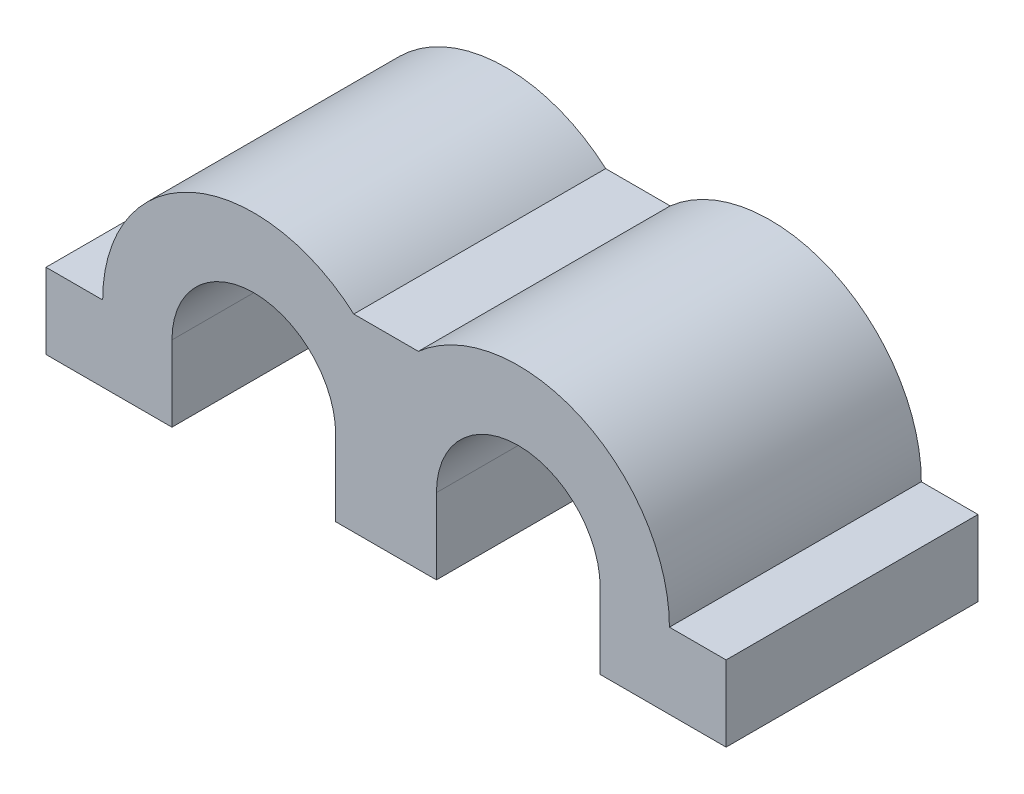
SolidWorks part; units mm, degrees
ref_plane "Front Plane" through (0, 0, 0) normal (0, 0, 1) x (1, 0, 0)
ref_plane "Top Plane" through (0, 0, 0) normal (0, 1, 0) x (1, 0, 0)
ref_plane "Right Plane" through (0, 0, 0) normal (1, 0, 0) x (0, 0, -1)
sketch "Sketch1" plane through (0, 0, 0) normal (0, 0, 1) x (1, 0, 0)
  line L0 (-138.8761, 0) -> (151.9065, 0) construction
  line L1 (0, 94.9844) -> (0, -89.4979) construction
  line L4 (8.5, 0) -> (13.5, 0)
  line L5 (-9.2587, 4.5) -> (22.6151, 4.5) construction
  line L8 (-1.2814, 4.5) -> (1.2814, 4.5)
  line L11 (-8.5, 0) -> (-8.5, -3)
  line L12 (-16.7652, -3) -> (21.656, -3) construction
  line L13 (-13.5, 0) -> (-13.5, -3)
  line L14 (-13.5, -3) -> (-8.5, -3)
  line L15 (-2, 0) -> (-2, -3)
  line L16 (-2, -3) -> (2, -3)
  line L17 (2, -3) -> (2, 0)
  line L18 (8.5, 0) -> (8.5, -3)
  line L19 (8.5, -3) -> (13.5, -3)
  line L20 (13.5, -3) -> (13.5, 0)
  line L21 (-13.5, 0) -> (-11.25, 0)
  line L22 (11.25, 0) -> (13.5, 0)
  arc A0 (-8.5, 0) -> (-2, 0) centre (-5.25, 0) cw
  arc A1 (2, 0) -> (8.5, 0) centre (5.25, 0) cw
  arc A2 (-1.2814, 4.5) -> (-11.25, 0) centre (-5.25, 0) ccw
  arc A3 (1.2814, 4.5) -> (11.25, 0) centre (5.25, 0) cw
  point P22 (0, 4.5)
  dimension "D6" = 6
  dimension "D1" = 5
  dimension "D3" = 4
  dimension "D4" = 6.5
  dimension "D5" = 6.5
  dimension "D8" = 4.5
  dimension "D9" = 3
extrude "Boss-Extrude1" add sketch "Sketch1" along normal blind 10
